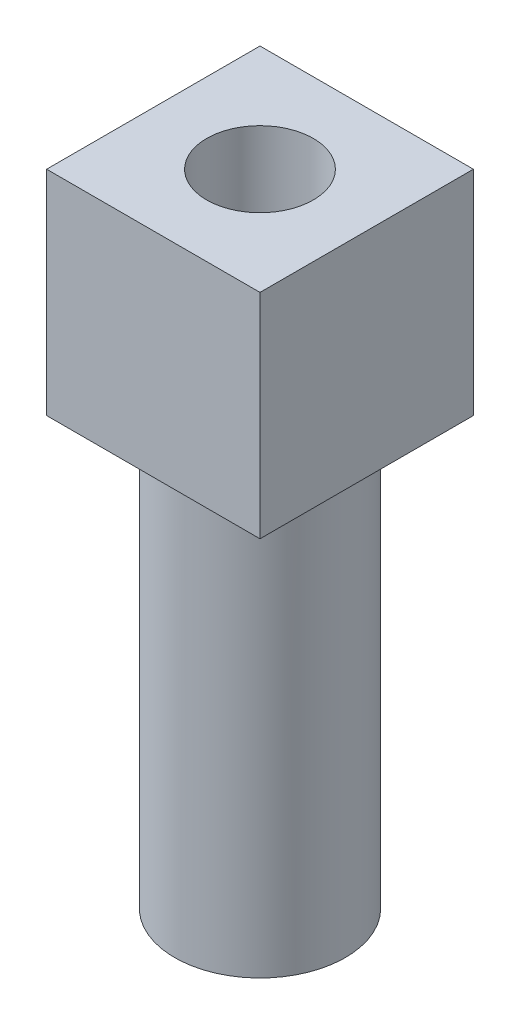
SolidWorks part; units mm, degrees
ref_plane "Ebene vorne" through (0, 0, 0) normal (0, 0, 1) x (1, 0, 0)
ref_plane "Ebene oben" through (0, 0, 0) normal (0, 1, 0) x (1, 0, 0)
ref_plane "Ebene rechts" through (0, 0, 0) normal (1, 0, 0) x (0, 0, -1)
sketch "Skizze1" plane through (0, 0, 0) normal (0, 0, 1) x (1, 0, 0)
  line L0 (0, 0) -> (4, 0)
  line L1 (4, 0) -> (4, 20)
  line L2 (0, 20) -> (4, 20)
  line L4 (0, -2.4593) -> (0, 22.5998) construction
  line L6 (0, 20) -> (0, 0)
  dimension "D1" = 4
  dimension "D2" = 20
revolve "Rotation1" add sketch "Skizze1" angle 360 about L4
sketch "Skizze5" plane through (0, 20, 0) normal (0, 1, 0) x (1, 0, 0)
  line L0 (0, 5) -> (0, -5) construction
  line L1 (-5, 5) -> (5, 5)
  line L2 (-5, 5) -> (-5, -5)
  line L3 (-5, -5) -> (5, -5)
  line L4 (5, 5) -> (5, -5)
  line L5 (5, 0) -> (-5, 0) construction
  dimension "D1" = 10
extrude "Aufsatz-Linear austragen1" add sketch "Skizze5" along normal blind 10
sketch "Sketch1" plane through (0, 30, 0) normal (0, 1, 0) x (1, 0, 0)
  circle A0 centre (0, 0) radius 2.5
extrude "Cut-Extrude1" cut sketch "Sketch1" against normal through all
